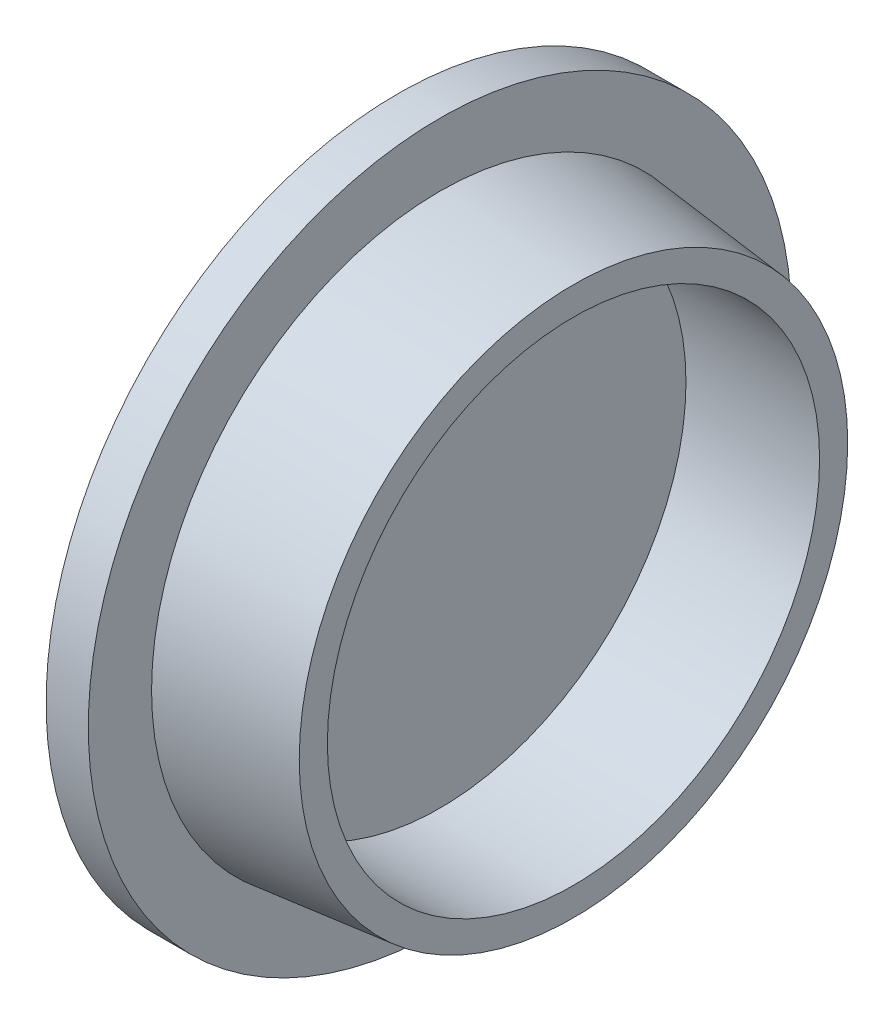
SolidWorks part; units mm, degrees
ref_plane "前视基准面" through (0, 0, 0) normal (0, 0, 1) x (1, 0, 0)
ref_plane "上视基准面" through (0, 0, 0) normal (0, 1, 0) x (1, 0, 0)
ref_plane "右视基准面" through (0, 0, 0) normal (1, 0, 0) x (0, 0, -1)
other "Configuration Table"
sketch "草图1" plane through (0, 0, 0) normal (0, 0, 1) x (1, 0, 0)
  line L0 (-1.9, 0) -> (-2.5, 0)
  line L1 (-2.5, 3.5) -> (-2.5, 5)
  line L2 (-2.5, 5) -> (-1.9, 5)
  line L3 (-1.9, 5) -> (-1.9, 4.1)
  line L5 (0, 3.9) -> (0, 3.5)
  line L6 (0, 3.5) -> (-1.9, 3.5)
  line L7 (-1.9, 4.1) -> (0, 3.9)
  line L8 (-2.5, 3.5) -> (-2.5, 0)
  line L9 (-2.5, 0) -> (-1.9, 0)
  line L10 (-1.9, 0) -> (-1.9, 3.5)
  dimension "D1" = 0.6
  dimension "D2" = 3.9
  dimension "D3" = 4.1
  dimension "D4" = 3.5
  dimension "D5" = 5
  dimension "D6" = 2.5
revolve "旋转1" add sketch "草图1" angle 360 about L0
